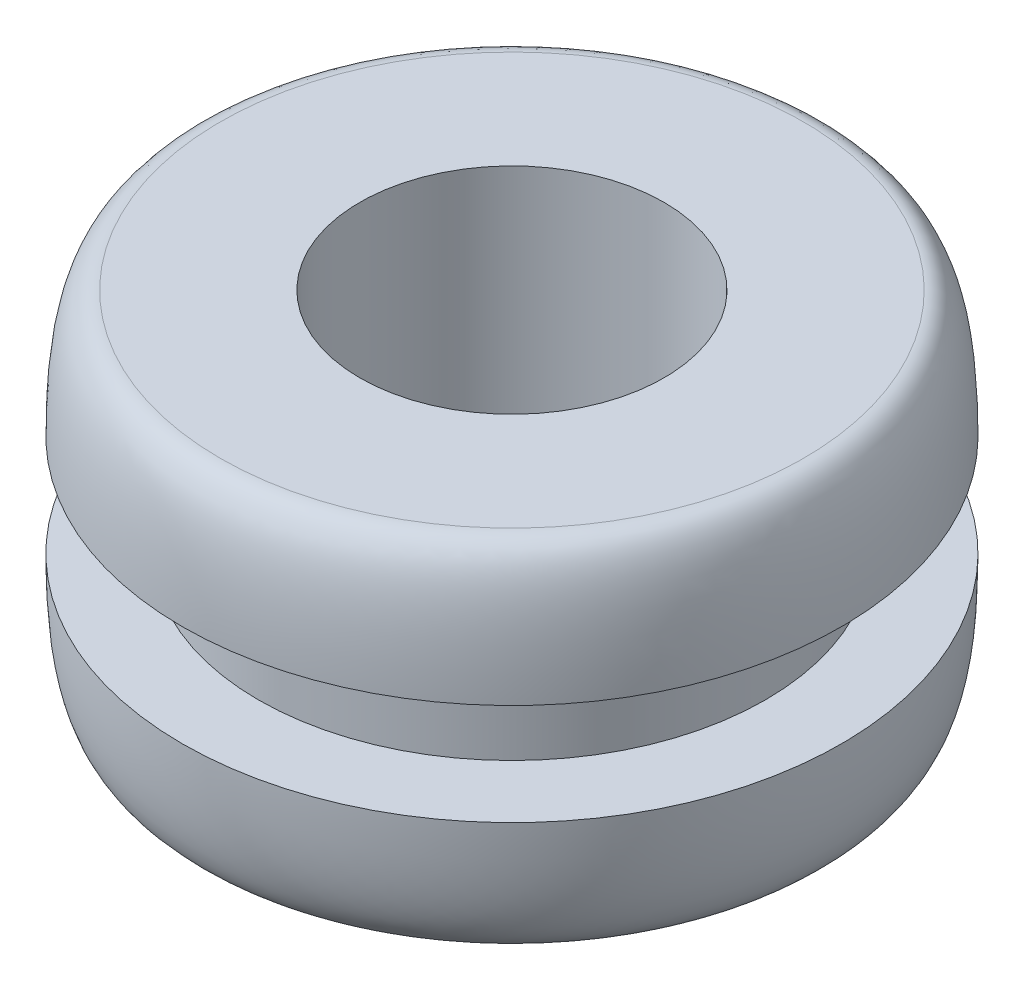
SolidWorks part; units mm, degrees
ref_plane "Front" through (0, 0, 0) normal (0, 0, 1) x (1, 0, 0)
ref_plane "Top" through (0, 0, 0) normal (0, 1, 0) x (1, 0, 0)
ref_plane "Right" through (0, 0, 0) normal (1, 0, 0) x (0, 0, -1)
sketch "Sketch1" plane through (0, 0, 0) normal (0, 0, 1) x (1, 0, 0)
  line L0 (-2.3813, 2.7781) -> (-2.3813, -2.7781)
  line L1 (-5.1594, 0.7937) -> (-3.9687, 0.7938)
  line L2 (-3.9687, 0.7938) -> (-3.9687, -0.7938)
  line L3 (-2.3813, -2.7781) -> (-4.5641, -2.7781)
  line L4 (-2.3813, 2.7781) -> (-4.5641, 2.7781)
  line L5 (-4.5641, 2.7781) -> (-4.5641, 0.7937) construction
  line L6 (-27.8997, 0) -> (0, 0) construction
  line L7 (55, 0) -> (-55, 0) construction
  line L8 (-5.1594, -0.7937) -> (-3.9687, -0.7938)
  line L9 (-5.1594, -0.056) -> (-5.1594, 2.4378) construction
  line L10 (-12.0259, 2.7781) -> (-10.1926, 2.7781) construction
  line L11 (0, 96.2646) -> (0, -76.2636) construction
  line L12 (0, -55) -> (0, 55) construction
  spline S0 degree 3 poles (-4.5641, 2.7781) (-5.0424, 2.7781) (-5.1594, 1.8328) (-5.1594, 0.7937) knots 0 0 0 0 1 1 1 1
  spline S1 degree 3 poles (-4.5641, -2.7781) (-5.0424, -2.7781) (-5.1594, -1.8328) (-5.1594, -0.7937) knots 0 0 0 0 1 1 1 1
  point P17 (-3.9687, 0)
  dimension "D1" = 1.5875
  dimension "D2" = 3.9688
  dimension "D3" = 2.3813
  dimension "D4" = 5.5562
  dimension "D5" = 5.1594
revolve "Revolve1" add sketch "Sketch1" angle 360 about L11
